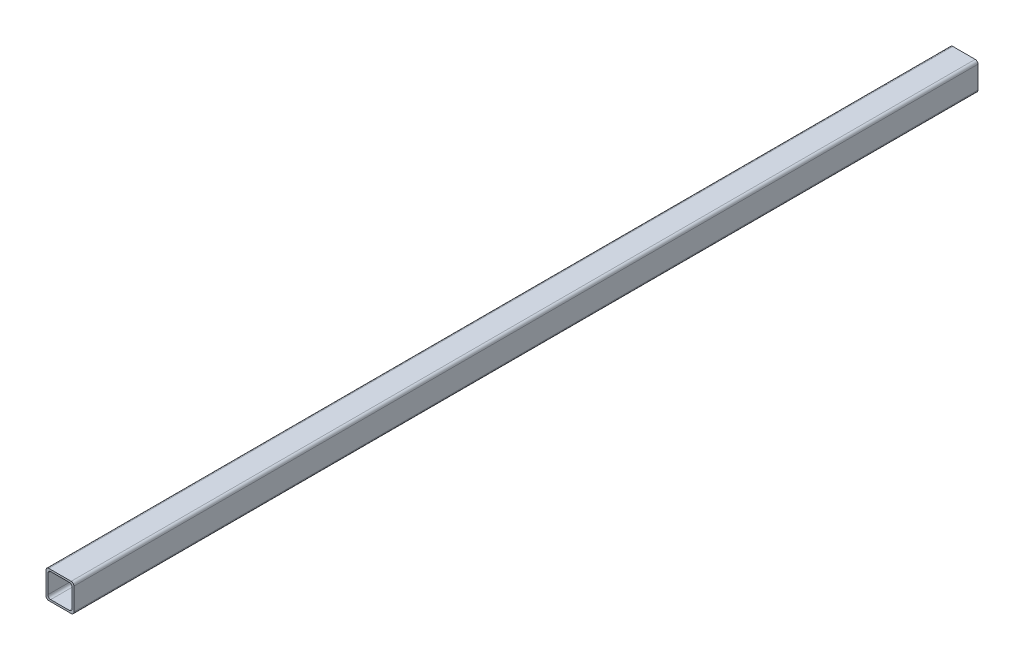
SolidWorks part; units mm, degrees
ref_plane "Plan de face" through (0, 0, 0) normal (0, 0, 1) x (1, 0, 0)
ref_plane "Plan de dessus" through (0, 0, 0) normal (0, 1, 0) x (1, 0, 0)
ref_plane "Plan de droite" through (0, 0, 0) normal (1, 0, 0) x (0, 0, -1)
sketch "Esquisse1" plane through (0, 0, 0) normal (0, 0, 1) x (1, 0, 0)
  line L1 (-12, -15) -> (12, -15)
  line L2 (-15, -12) -> (-15, 12)
  line L3 (-12, 15) -> (12, 15)
  line L4 (15, -12) -> (15, 12)
  line L5 (0, 15) -> (0, -15) construction
  line L6 (-15, 0) -> (15, 0) construction
  line L7 (-10, -13) -> (10, -13)
  line L8 (-13, -10) -> (-13, 10)
  line L9 (-10, 13) -> (10, 13)
  line L10 (13, -10) -> (13, 10)
  line L11 (0, 13) -> (0, -13) construction
  line L12 (-13, 0) -> (13, 0) construction
  arc A0 (10, -13) -> (13, -10) centre (10, -10) ccw
  arc A1 (12, -15) -> (15, -12) centre (12, -12) ccw
  arc A2 (-13, 10) -> (-10, 13) centre (-10, 10) cw
  arc A3 (-10, -13) -> (-13, -10) centre (-10, -10) cw
  arc A4 (10, 13) -> (13, 10) centre (10, 10) cw
  arc A5 (-15, 12) -> (-12, 15) centre (-12, 12) cw
  arc A6 (-12, -15) -> (-15, -12) centre (-12, -12) cw
  arc A7 (12, 15) -> (15, 12) centre (12, 12) cw
  point P0 (0, 0)
  point P4 (0, 0)
  point P20 (-13, 13)
  point P25 (13, 13)
  point P28 (-15, 15)
  point P33 (15, 15)
  dimension "D5" = 3
  dimension "D1" = 30
  dimension "D2" = 26
  dimension "D3" = 30
  dimension "D4" = 26
extrude "Boss.-Extru.1" add sketch "Esquisse1" against normal blind 970
